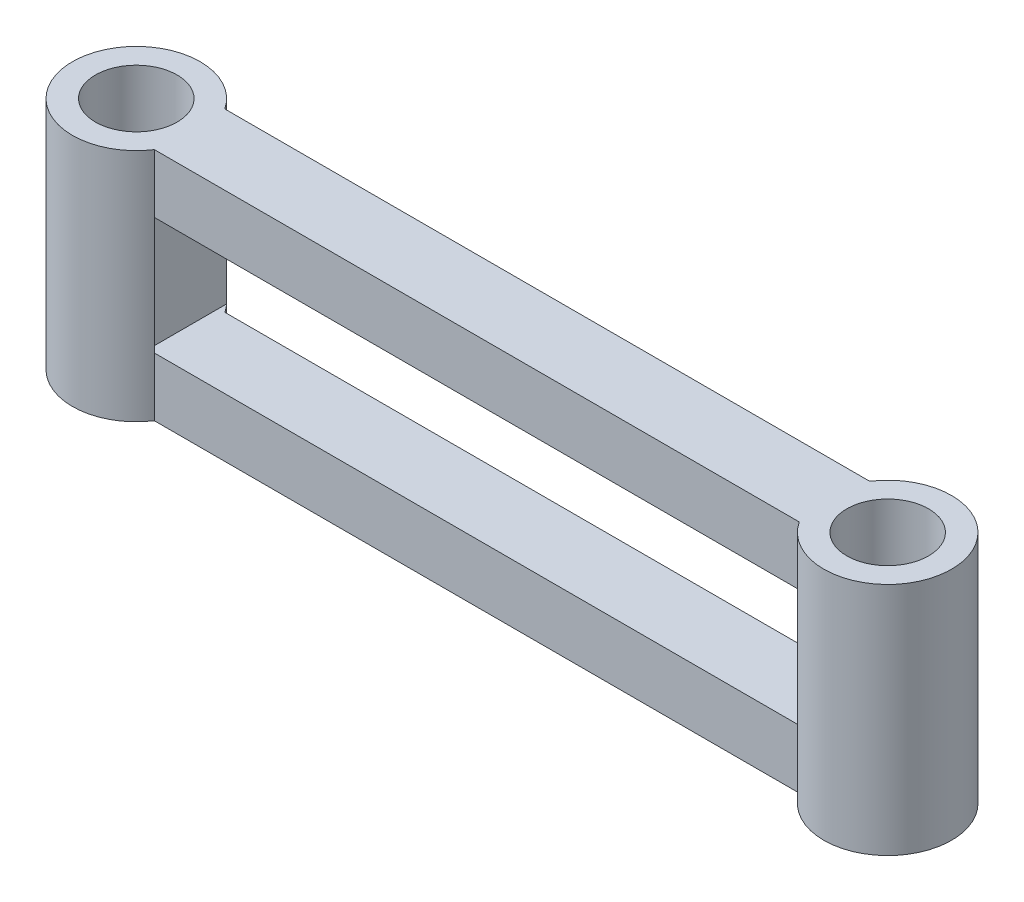
SolidWorks part; units mm, degrees
ref_plane "Front Plane" through (0, 0, 0) normal (0, 0, 1) x (1, 0, 0)
ref_plane "Top Plane" through (0, 0, 0) normal (0, 1, 0) x (1, 0, 0)
ref_plane "Right Plane" through (0, 0, 0) normal (1, 0, 0) x (0, 0, -1)
sketch "Sketch1" plane through (0, 0, 0) normal (0, 1, 0) x (1, 0, 0)
  line L0 (-101.6, 49.5042) -> (-87.1918, 59.0292) construction
  line L5 (-101.6, 49.5042) -> (-87.1918, 39.9792) construction
  line L6 (101.6, 49.5042) -> (87.1918, 59.0292) construction
  line L7 (101.6, 49.5042) -> (87.1918, 39.9792) construction
  line L8 (-87.1918, 59.0292) -> (87.1918, 59.0292)
  line L9 (-87.1918, 39.9792) -> (87.1918, 39.9792)
  circle A1 centre (101.6, 49.5042) radius 11.049
  circle A2 centre (-101.6, 49.5042) radius 11.049
  arc A3 (-87.1918, 59.0292) -> (-87.1918, 39.9792) centre (-101.6, 49.5042) ccw
  arc A4 (87.1918, 39.9792) -> (87.1918, 59.0292) centre (101.6, 49.5042) ccw
  point P0 (118.872, 49.5042)
  point P1 (-118.872, 49.5042)
  dimension "D1" = 203.2
  dimension "D3" = 19.05
  dimension "D9" = 22.098
  dimension "D10" = 22.098
  dimension "D2" = 17.272
  dimension "D4" = 19.05
  dimension "D5" = 17.272
  dimension "D6" = 0
  dimension "D7" = 0
  dimension "D8" = 101.6
extrude "Boss-Extrude1" add sketch "Sketch1" along normal blind 63.5
sketch "Sketch2" plane through (0, 0, -39.9792) normal (0, 0, 1) x (1, 0, 0)
  line L1 (-88.9, 47.625) -> (88.9, 47.625)
  line L2 (-88.9, 47.625) -> (-88.9, 15.875)
  line L3 (-88.9, 15.875) -> (88.9, 15.875)
  line L4 (88.9, 47.625) -> (88.9, 15.875)
  dimension "D1" = 31.75
  dimension "D2" = 177.8
  dimension "D3" = 88.9
  dimension "D4" = 15.875
extrude "Cut-Extrude1" cut sketch "Sketch2" against normal through all
